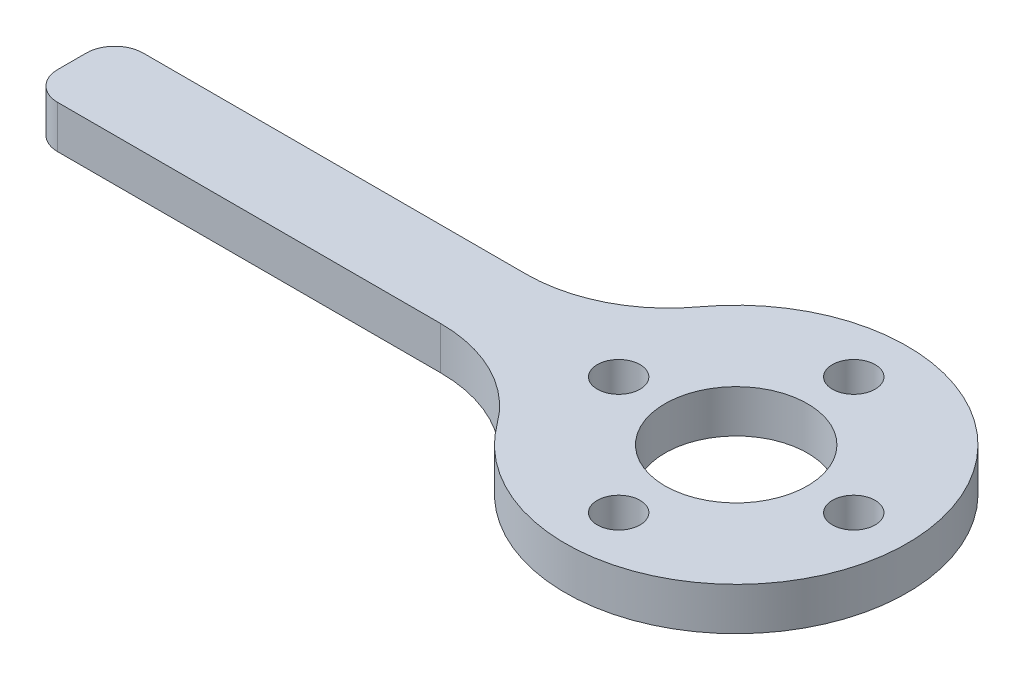
SolidWorks part; units mm, degrees
material "Thornel Mat VMA"
ref_plane "前视基准面" through (0, 0, 0) normal (0, 0, 1) x (1, 0, 0)
ref_plane "上视基准面" through (0, 0, 0) normal (0, 1, 0) x (1, 0, 0)
ref_plane "右视基准面" through (0, 0, 0) normal (1, 0, 0) x (0, 0, -1)
sketch "草图1" plane through (0, 0, 0) normal (0, 1, 0) x (1, 0, 0)
  line L0 (0, 12) -> (0, -12) construction
  line L1 (-11.619, -3) -> (-11.619, 3) construction
  line L3 (-11.619, -3) -> (-46.619, -3)
  line L4 (-46.619, -3) -> (-46.619, 3)
  line L5 (-46.619, 3) -> (-11.619, 3)
  arc A0 (-11.619, -3) -> (-11.619, 3) centre (0, 0) ccw
  circle A1 centre (0, 0) radius 5
  dimension "D1" = 24
  dimension "D2" = 10
  dimension "D3" = 6
  dimension "D4" = 35
extrude "凸台-拉伸1" add sketch "草图1" along normal blind 3
sketch "草图2" plane through (0, 3, 0) normal (0, 1, 0) x (1, 0, 0)
  line L0 (0, 0) -> (0, 8.25) construction
  line L1 (-11.619, 3) -> (-46.619, 3) construction
  circle A0 centre (0, 8.25) radius 1.5
  circle A1 centre (8.25, 0) radius 1.5
  circle A2 centre (0, -8.25) radius 1.5
  circle A3 centre (-8.25, 0) radius 1.5
  point P15 (0, 0)
  dimension "D2" = 3
  dimension "D1" = 8.25
  dimension "D3" = 4
extrude "切除-拉伸1" cut sketch "草图2" against normal through all
fillet "圆角1" radius 2 2 edges at (-46.619, 1.5, -3) (-46.619, 1.5, 3)
fillet "圆角2" radius 10 2 edges at (-11.619, 1.5, 3) (-11.619, 1.5, -3)
sketch "草图3" plane through (0, 3, 0) normal (0, 1, 0) x (1, 0, 0)
  line L0 (0, 0) -> (-31.69, 0) construction
  circle A0 centre (-31.69, 0) radius 1.5
  dimension "D2" = 3
  dimension "D1" = 31.69
